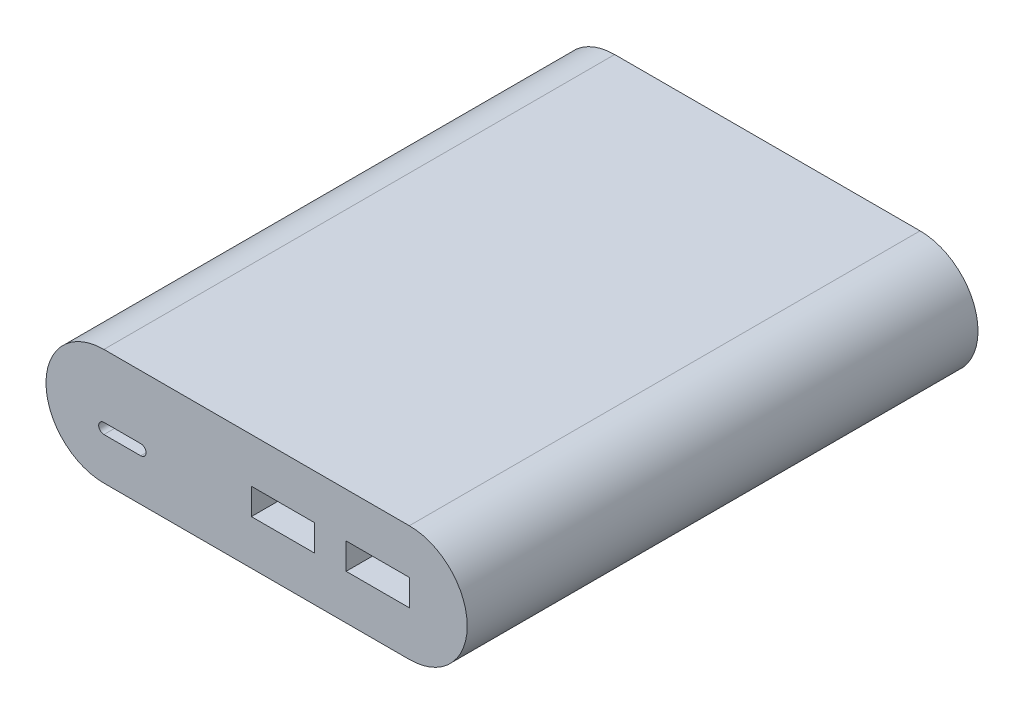
SolidWorks part; units mm, degrees
ref_plane "Plan de face" through (0, 0, 0) normal (0, 0, 1) x (1, 0, 0)
ref_plane "Plan de dessus" through (0, 0, 0) normal (0, 1, 0) x (1, 0, 0)
ref_plane "Plan de droite" through (0, 0, 0) normal (1, 0, 0) x (0, 0, -1)
sketch "Esquisse1" plane through (0, 0, 0) normal (0, 0, 1) x (1, 0, 0)
  line L0 (0, 0) -> (58, 0) construction
  line L1 (0, 11) -> (58, 11)
  line L2 (0, -11) -> (58, -11)
  arc A0 (0, 11) -> (0, -11) centre (0, 0) ccw
  arc A1 (58, -11) -> (58, 11) centre (58, 0) ccw
  point P3 (29, 0)
extrude "Boss.-Extru.1" add sketch "Esquisse1" along normal blind 97
sketch "Esquisse2" plane through (0, 0, 97) normal (0, 0, 1) x (1, 0, 0)
  line L0 (0, -2) -> (7, -2) construction
  line L1 (0, -1) -> (7, -1)
  line L2 (0, -3) -> (7, -3)
  line L3 (0, -11) -> (58, -11) construction
  line L4 (58, 11) -> (58, -11) construction
  line L5 (-11, 0) -> (69, 0) construction
  line L7 (46, -2.5) -> (58, -2.5)
  line L8 (46, -2.5) -> (46, 2.5)
  line L9 (46, 2.5) -> (58, 2.5)
  line L10 (58, -2.5) -> (58, 2.5)
  line L11 (46, -2.5) -> (58, 2.5) construction
  line L12 (46, 2.5) -> (58, -2.5) construction
  line L13 (28, -2.5) -> (40, -2.5)
  line L14 (28, -2.5) -> (28, 2.5)
  line L15 (28, 2.5) -> (40, 2.5)
  line L16 (40, -2.5) -> (40, 2.5)
  line L17 (28, -2.5) -> (40, 2.5) construction
  line L18 (28, 2.5) -> (40, -2.5) construction
  arc A0 (0, -1) -> (0, -3) centre (0, -2) ccw
  arc A1 (7, -3) -> (7, -1) centre (7, -2) ccw
  arc A2 (0, 11) -> (0, -11) centre (0, 0) ccw construction
  arc A3 (58, -11) -> (58, 11) centre (58, 0) ccw construction
  point P2 (3.5, -2)
  point P14 (52, 0)
  point P19 (34, 0)
  dimension "D1" = 9
  dimension "D6" = 12
  dimension "D2" = 5
  dimension "D3" = 12
  dimension "D4" = 6
  dimension "D5" = 5
extrude "Enlèv. mat.-Extru.1" cut sketch "Esquisse2" against normal blind 10
